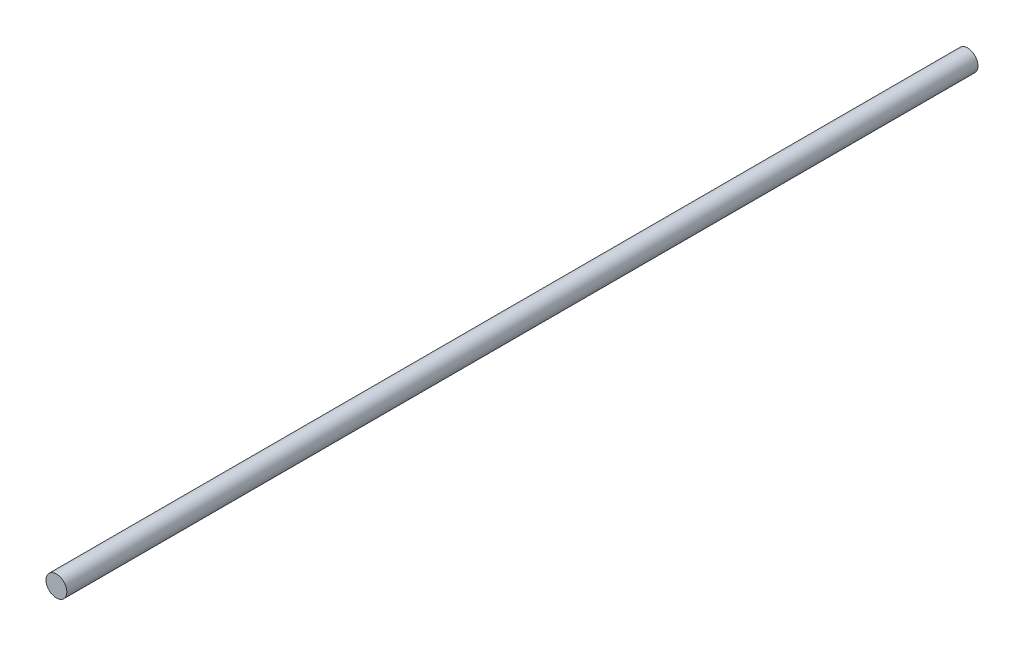
SolidWorks part; units mm, degrees
ref_plane "Front Plane" through (0, 0, 0) normal (0, 0, 1) x (1, 0, 0)
ref_plane "Top Plane" through (0, 0, 0) normal (0, 1, 0) x (1, 0, 0)
ref_plane "Right Plane" through (0, 0, 0) normal (1, 0, 0) x (0, 0, -1)
sketch "Sketch1" plane through (0, 0, 0) normal (0, 0, 1) x (1, 0, 0)
  circle A0 centre (0, 0) radius 4
  dimension "D1" = 8
extrude "Boss-Extrude1" add sketch "Sketch1" along normal blind 350
sketch "Sketch2" plane through (0, 0, 0) normal (0, 1, 0) x (1, 0, 0)
  line L0 (0, -174.8988) -> (22.3799, -174.8988) construction
  line L1 (0, -350) -> (0, 0) construction
ref_plane "Plane1" through (0, 0, 200) normal (0, 0, 1) x (1, 0, 0)
sketch "Sketch4" plane through (0, 0, 200) normal (0, 0, 1) x (1, 0, 0)
  line L0 (0, 0) -> (0, 4)
  circle A0 centre (0, 0) radius 4
